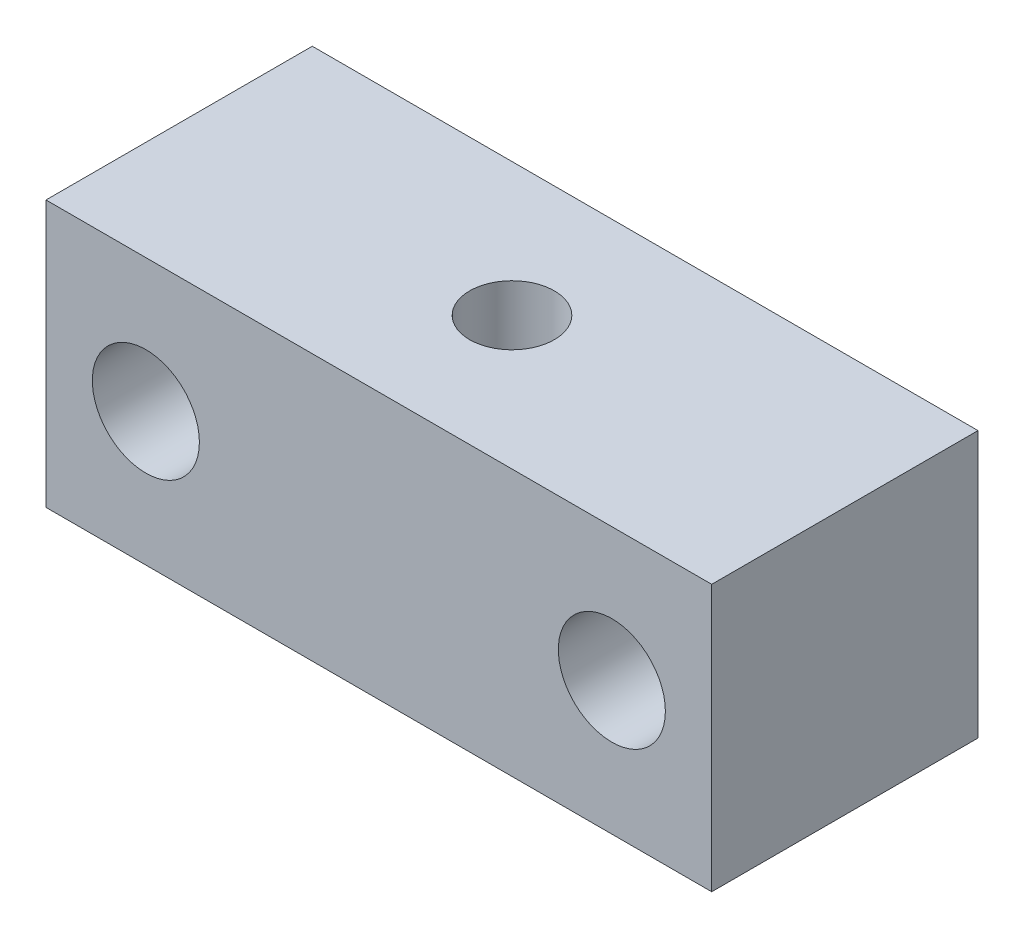
SolidWorks part; units mm, degrees
material "6061-T6 (SS)"
ref_plane "Front Plane" through (0, 0, 0) normal (0, 0, 1) x (1, 0, 0)
ref_plane "Top Plane" through (0, 0, 0) normal (0, 1, 0) x (1, 0, 0)
ref_plane "Right Plane" through (0, 0, 0) normal (1, 0, 0) x (0, 0, -1)
sketch "Sketch1" plane through (0, 0, 0) normal (0, 0, 1) x (1, 0, 0)
  line L1 (0, 0) -> (31.75, 0)
  line L2 (0, 0) -> (0, 12.7)
  line L3 (0, 12.7) -> (31.75, 12.7)
  line L4 (31.75, 0) -> (31.75, 12.7)
  dimension "D1" = 12.7
  dimension "D2" = 31.75
extrude "Boss-Extrude1" add sketch "Sketch1" along normal mid plane 12.7
sketch "Sketch2" plane through (0, 0, 6.35) normal (0, 0, 1) x (1, 0, 0)
  line L0 (0, 6.35) -> (31.75, 6.35) construction
  line L1 (0, 12.7) -> (0, 0) construction
  line L2 (31.75, 0) -> (31.75, 12.7) construction
  circle A0 centre (4.7625, 6.35) radius 2.5527
  circle A1 centre (26.9875, 6.35) radius 2.5527
  dimension "D1" = 5.1054
  dimension "D3" = 4.7625
extrude "Cut-Extrude1" cut sketch "Sketch2" against normal through all
hole_wizard "#10-32 Tapped Hole1" positions "3DSketch1" profile "Sketch3" tap size "#10-32" standard "ANSI Inch" end condition through all
sketch3d "3DSketch1"
  line L0 (0, 12.7, 0) -> (31.75, 12.7, 0) construction
  line L1 (0, 12.7, 6.35) -> (0, 12.7, -6.35) construction
  line L2 (31.75, 12.7, 6.35) -> (31.75, 12.7, -6.35) construction
  line L5 (15.875, 12.7, 6.35) -> (15.875, 12.7, -6.35) construction
  line L6 (31.75, 12.7, 6.35) -> (0, 12.7, 6.35) construction
  line L7 (31.75, 12.7, -6.35) -> (0, 12.7, -6.35) construction
  point P0 (15.875, 12.7, 0)
  point P20 (17.042, 12.7, 1.249)
  point P21 (15.875, 12.7, 0)
  point P22 (15.875, 12.7, 0)
sketch "Sketch3" plane through (15.875, 12.7, 0) normal (1, 0, 0) x (0, 0, 1)
  line L0 (0, 0) -> (0, 12.7)
  line L1 (0, 12.7) -> (2.0193, 12.7)
  line L2 (2.0193, 12.7) -> (2.0193, 0)
  line L5 (2.0193, 0) -> (0, 0)
  line L11 (0, -6.35) -> (0, 107.95) construction
  dimension "Thru Tap Drill Dia." = 4.0386
  dimension "Thru Tap Drill Depth" = 12.7
cosmetic thread "Hole Thread1"
equation "\"D3@Sketch2\"=\"D2@Sketch2\""
